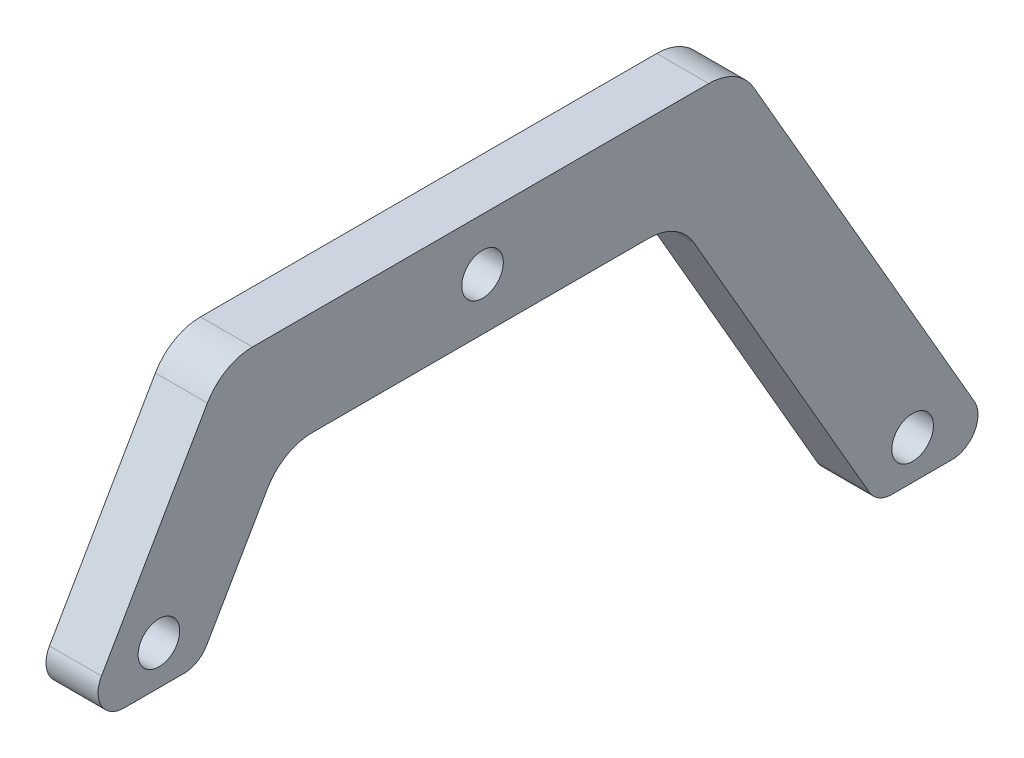
SolidWorks part; units mm, degrees
ref_plane "Front Plane" through (0, 0, 0) normal (0, 0, 1) x (1, 0, 0)
ref_plane "Top Plane" through (0, 0, 0) normal (0, 1, 0) x (1, 0, 0)
ref_plane "Right Plane" through (0, 0, 0) normal (1, 0, 0) x (0, 0, -1)
sketch "Sketch1" plane through (0, 0, 0) normal (1, 0, 0) x (0, 0, -1)
  line L0 (-119.1784, 67.0522) -> (-78.4621, 137.5749)
  line L1 (-61.1416, 147.5749) -> (114.2283, 147.5749)
  line L2 (131.5488, 137.5749) -> (216.4151, -9.4178)
  line L3 (207.7548, -24.4178) -> (184.6608, -24.4178)
  line L4 (176.0006, -19.4178) -> (108.4548, 97.5749)
  line L5 (91.1343, 107.5749) -> (-38.0476, 107.5749)
  line L6 (-55.3681, 97.5749) -> (-78.7639, 57.0522)
  line L7 (-87.4241, 52.0522) -> (-110.5181, 52.0522)
  arc A0 (114.2283, 147.5749) -> (131.5488, 137.5749) centre (114.2283, 127.5749) cw
  arc A1 (108.4548, 97.5749) -> (91.1343, 107.5749) centre (91.1343, 87.5749) ccw
  arc A2 (-38.0476, 107.5749) -> (-55.3681, 97.5749) centre (-38.0476, 87.5749) ccw
  arc A3 (-78.4621, 137.5749) -> (-61.1416, 147.5749) centre (-61.1416, 127.5749) cw
  arc A4 (216.4151, -9.4178) -> (207.7548, -24.4178) centre (207.7548, -14.4178) cw
  arc A5 (184.6608, -24.4178) -> (176.0006, -19.4178) centre (184.6608, -14.4178) cw
  arc A6 (-78.7639, 57.0522) -> (-87.4241, 52.0522) centre (-87.4241, 62.0522) cw
  arc A7 (-119.1784, 67.0522) -> (-110.5181, 52.0522) centre (-110.5181, 62.0522) ccw
  circle A8 centre (27.2934, 127.5749) radius 8
  circle A9 centre (-97.1009, 67.0522) radius 8
  circle A10 centre (192.6209, -9.4178) radius 8
  point P11 (125.7753, 147.5749)
  point P16 (-49.5946, 107.5749)
  point P19 (-72.6886, 147.5749)
  point P22 (225.0753, -24.4178)
  dimension "D7" = 20
  dimension "D8" = 10
  dimension "D9" = 16
  dimension "D1" = 198.6
  dimension "D2" = 120
  dimension "D3" = 40
  dimension "D4" = 40
  dimension "D5" = 40
  dimension "D6" = 120
extrude "Boss-Extrude1" add sketch "Sketch1" along normal blind 20
